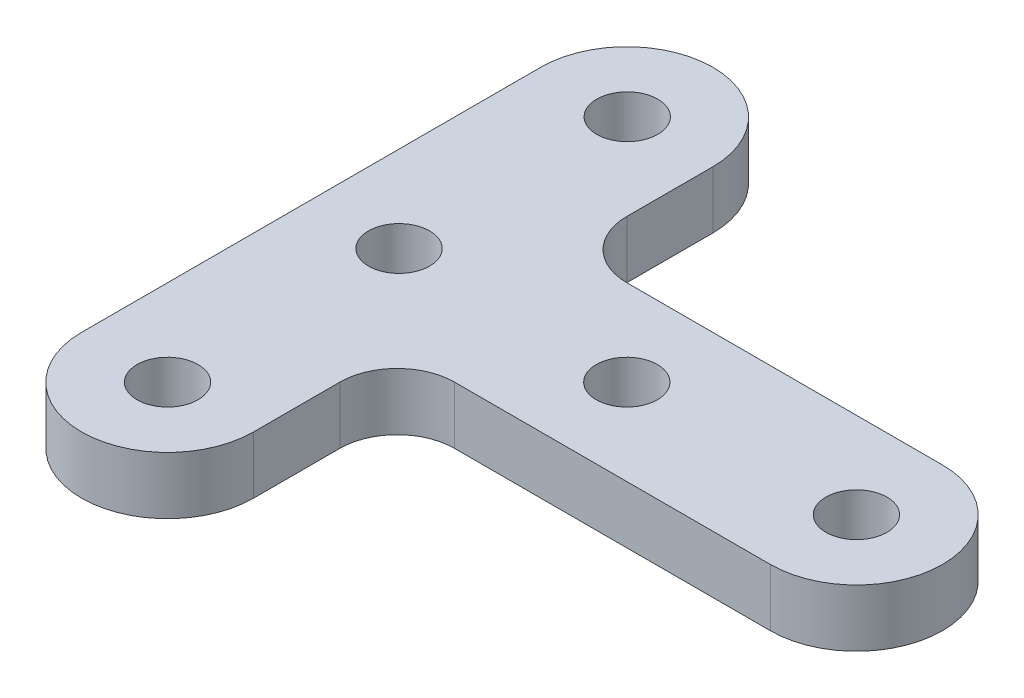
SolidWorks part; units mm, degrees
ref_plane "Front Plane" through (0, 0, 0) normal (0, 0, 1) x (1, 0, 0)
ref_plane "Top Plane" through (0, 0, 0) normal (0, 1, 0) x (1, 0, 0)
ref_plane "Right Plane" through (0, 0, 0) normal (1, 0, 0) x (0, 0, -1)
sketch "Sketch1" plane through (0, 144.9046, 0) normal (0, -1, 0) x (-1, 0, 0)
  line L0 (-105.4418, -1122.1003) -> (-105.4418, -1137.9753) construction
  line L1 (-124.4918, -1137.9753) -> (-124.4918, -1087.1753) construction
  line L2 (-105.4418, -1103.0503) -> (-105.4418, -1087.1753) construction
  line L3 (-64.1668, -1103.0503) -> (-105.4418, -1103.0503) construction
  line L4 (-105.4418, -1122.1003) -> (-105.4418, -1137.9753)
  line L5 (-124.4918, -1137.9753) -> (-124.4918, -1087.1753)
  line L6 (-105.4418, -1103.0503) -> (-105.4418, -1087.1753)
  line L7 (-64.1668, -1103.0503) -> (-105.4418, -1103.0503)
  line L8 (-105.4418, -1122.1003) -> (-64.1668, -1122.1003)
  circle A0 centre (-114.9668, -1137.9753) radius 9.525 construction
  circle A1 centre (-64.1668, -1112.5753) radius 9.525 construction
  circle A2 centre (-114.9668, -1087.1753) radius 9.525 construction
  arc A3 (-124.4918, -1137.9753) -> (-105.4418, -1137.9753) centre (-114.9668, -1137.9753) ccw
  arc A4 (-64.1668, -1122.1003) -> (-64.1668, -1103.0503) centre (-64.1668, -1112.5753) ccw
  arc A5 (-105.4418, -1087.1753) -> (-124.4918, -1087.1753) centre (-114.9668, -1087.1753) ccw
extrude "Boss-Extrude1" add sketch "Sketch1" along normal up to vertex (19.177 mm away) from vertex at 12.827
hole_wizard "1/4 Clearance Hole1" positions "Sketch2" profile "Sketch3" hole size "1/4" standard "ANSI Inch" end condition through all
sketch "Sketch2" plane through (0, 125.7276, 0) normal (0, -1, 0) x (-1, 0, 0)
  point P0 (-114.9668, -1137.9753)
  point P3 (-114.9668, -1112.3692)
  point P5 (-114.9668, -1087.1288)
  point P7 (-64.1668, -1112.5753)
  point P10 (-89.5668, -1112.5753)
sketch "Sketch3" plane through (114.9668, 125.7276, 1137.9753) normal (1, 0, 0) x (0, 0, -1)
  line L0 (0, 0) -> (0, 6.35)
  line L1 (0, 6.35) -> (3.3782, 6.35)
  line L2 (3.3782, 6.35) -> (3.3782, 0)
  line L5 (3.3782, 0) -> (0, 0)
  line L11 (0, -6.35) -> (0, 107.95) construction
  dimension "Thru Hole Dia." = 6.7564
  dimension "Thru Hole Depth" = 6.35
mirror "Mirror1" about plane through (0, 0, 0) normal (1, 0, 0) of bodies 103 101
delete or keep bodies "Body-Delete/Keep 1" type delete bodies bodies 103
fillet "Fillet1" radius 6.35 2 edges at (-105.4418, 128.9026, 1103.0503) (-105.4418, 128.9026, 1122.1003)
